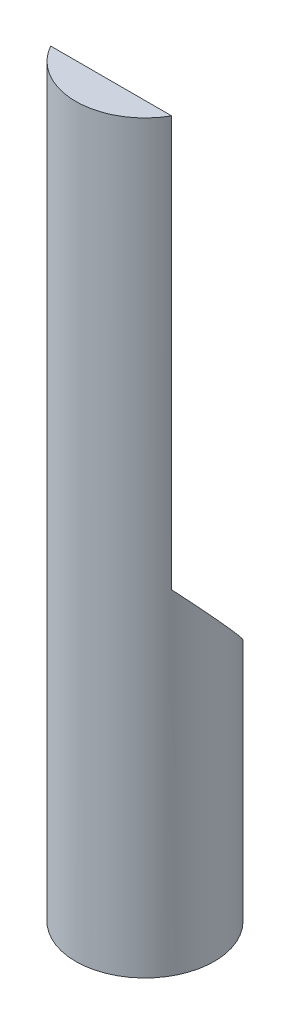
SolidWorks part; units mm, degrees
ref_plane "Front Plane" through (0, 0, 0) normal (0, 0, 1) x (1, 0, 0)
ref_plane "Top Plane" through (0, 0, 0) normal (0, 1, 0) x (1, 0, 0)
ref_plane "Right Plane" through (0, 0, 0) normal (1, 0, 0) x (0, 0, -1)
sketch "Sketch1" plane through (0, 0, 0) normal (0, 1, 0) x (1, 0, 0)
  circle A0 centre (0, 0) radius 3.9713
  dimension "D1" = 7.9426
extrude "Boss-Extrude1" add sketch "Sketch1" along normal blind 42.672
sketch "Sketch2" plane through (0, 0, 0) normal (1, 0, 0) x (0, 0, -1)
  line L0 (-3.9713, 40.162) -> (-3.9713, 46.9504) construction
  line L1 (-3.9713, 42.672) -> (-3.9713, 0) construction
  line L2 (-1.9393, 47.4841) -> (-1.9393, 19.1606)
  line L3 (-1.9393, 19.1606) -> (3.9713, 12.7)
  line L4 (3.9713, 12.7) -> (3.9713, 47.4841)
  line L5 (3.9713, 47.4841) -> (-1.9393, 47.4841)
  line L6 (-3.9713, 0) -> (3.9713, 0) construction
  line L7 (3.9713, 0) -> (3.9713, 42.672) construction
  dimension "D1" = 4.064
  dimension "D2" = 12.7
extrude "Cut-Extrude1" cut sketch "Sketch2" against normal through all and the other way through all
